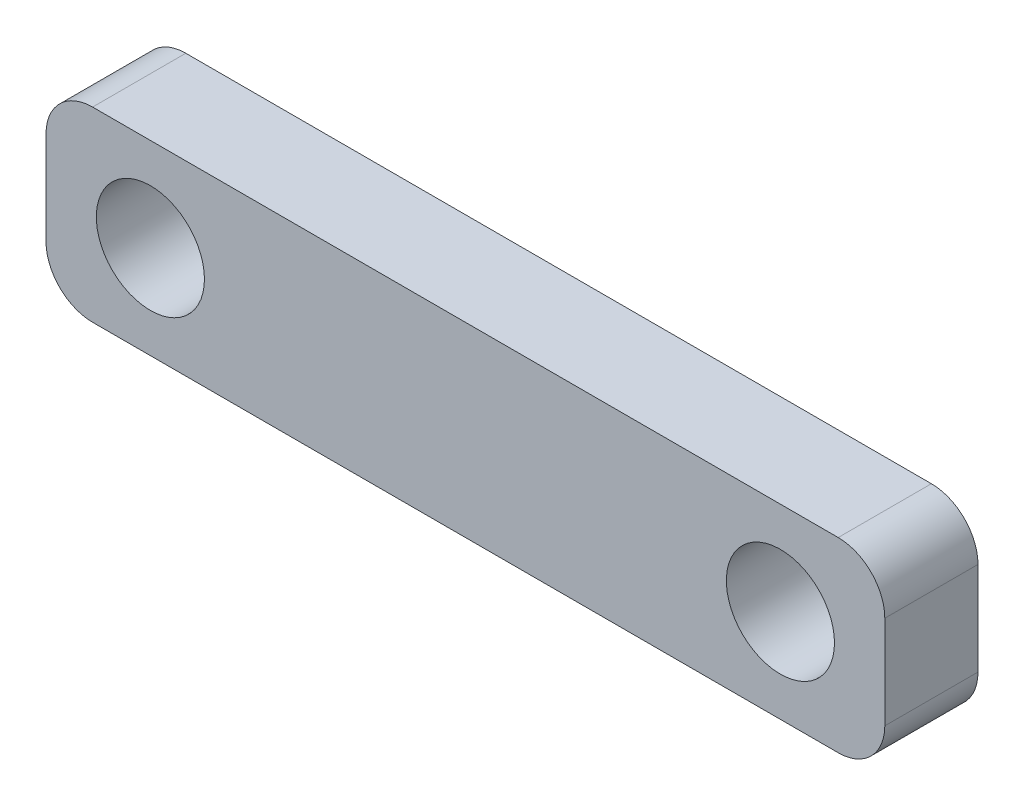
SolidWorks part; units mm, degrees
ref_plane "Front Plane" through (0, 0, 0) normal (0, 0, 1) x (1, 0, 0)
ref_plane "Top Plane" through (0, 0, 0) normal (0, 1, 0) x (1, 0, 0)
ref_plane "Right Plane" through (0, 0, 0) normal (1, 0, 0) x (0, 0, -1)
sketch "Sketch1" plane through (0, 0, 0) normal (0, 0, 1) x (1, 0, 0)
  line L1 (-7.1437, 1.5875) -> (7.1438, 1.5875)
  line L2 (-7.1437, 1.5875) -> (-7.1437, -1.5875)
  line L3 (-7.1437, -1.5875) -> (7.1437, -1.5875)
  line L4 (7.1438, 1.5875) -> (7.1437, -1.5875)
  line L5 (-7.1437, 1.5875) -> (7.1437, -1.5875) construction
  line L6 (-7.1437, -1.5875) -> (7.1438, 1.5875) construction
  point P0 (0, 0)
  dimension "D1" = 14.2875
  dimension "D2" = 3.175
extrude "Boss-Extrude1" add sketch "Sketch1" along normal blind 1.5875
sketch "Sketch2" plane through (0, 0, 1.5875) normal (0, 0, 1) x (1, 0, 0)
  line L0 (-7.1437, 0) -> (7.1437, 0) construction
  line L1 (-7.1437, 1.5875) -> (-7.1437, -1.5875) construction
  line L2 (7.1437, -1.5875) -> (7.1438, 1.5875) construction
  circle A0 centre (-5.3657, 0) radius 0.9207
  circle A1 centre (5.3657, 0) radius 0.9208
  point P10 (0, 0)
  point P11 (0, 0)
  dimension "D3" = 1.8415
  dimension "D1" = 1.778
  dimension "D2" = 1.778
extrude "Cut-Extrude1" cut sketch "Sketch2" against normal up to next
fillet "Fillet1" radius 0.7937 4 edges at (7.1437, -1.5875, 0.7937) (7.1438, 1.5875, 0.7937) (-7.1437, -1.5875, 0.7937) (-7.1437, 1.5875, 0.7937)
